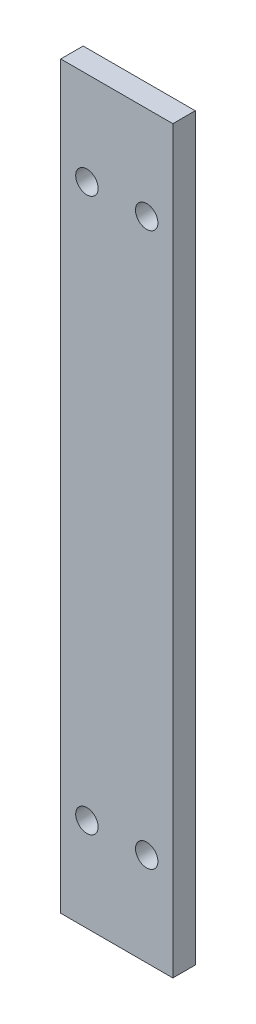
SolidWorks part; units mm, degrees
material "A-玻璃纤维"
ref_plane "前视基准面" through (0, 0, 0) normal (0, 0, 1) x (1, 0, 0)
ref_plane "上视基准面" through (0, 0, 0) normal (0, 1, 0) x (1, 0, 0)
ref_plane "右视基准面" through (0, 0, 0) normal (1, 0, 0) x (0, 0, -1)
sketch "草图1" plane through (0, 0, 0) normal (0, 0, 1) x (1, 0, 0)
  line L0 (-7.5, 37) -> (7.5, 37) construction
  line L1 (-7.5, 49.5) -> (7.5, 49.5)
  line L2 (-7.5, 49.5) -> (-7.5, -49.5)
  line L3 (-7.5, -49.5) -> (7.5, -49.5)
  line L4 (7.5, 49.5) -> (7.5, -49.5)
  line L5 (-7.5, 49.5) -> (7.5, -49.5) construction
  line L6 (-7.5, -49.5) -> (7.5, 49.5) construction
  line L7 (-7.5, 0) -> (7.5, 0) construction
  line L8 (0, 49.5) -> (0, 0) construction
  circle A0 centre (-4, 37) radius 1.5
  circle A1 centre (4, 37) radius 1.5
  circle A2 centre (4, -37) radius 1.5
  circle A3 centre (-4, -37) radius 1.5
  point P0 (0, 0)
  dimension "D4" = 4
  dimension "D5" = 3
  dimension "D1" = 15
  dimension "D2" = 99
  dimension "D3" = 12.5
extrude "凸台-拉伸1" add sketch "草图1" along normal blind 3
